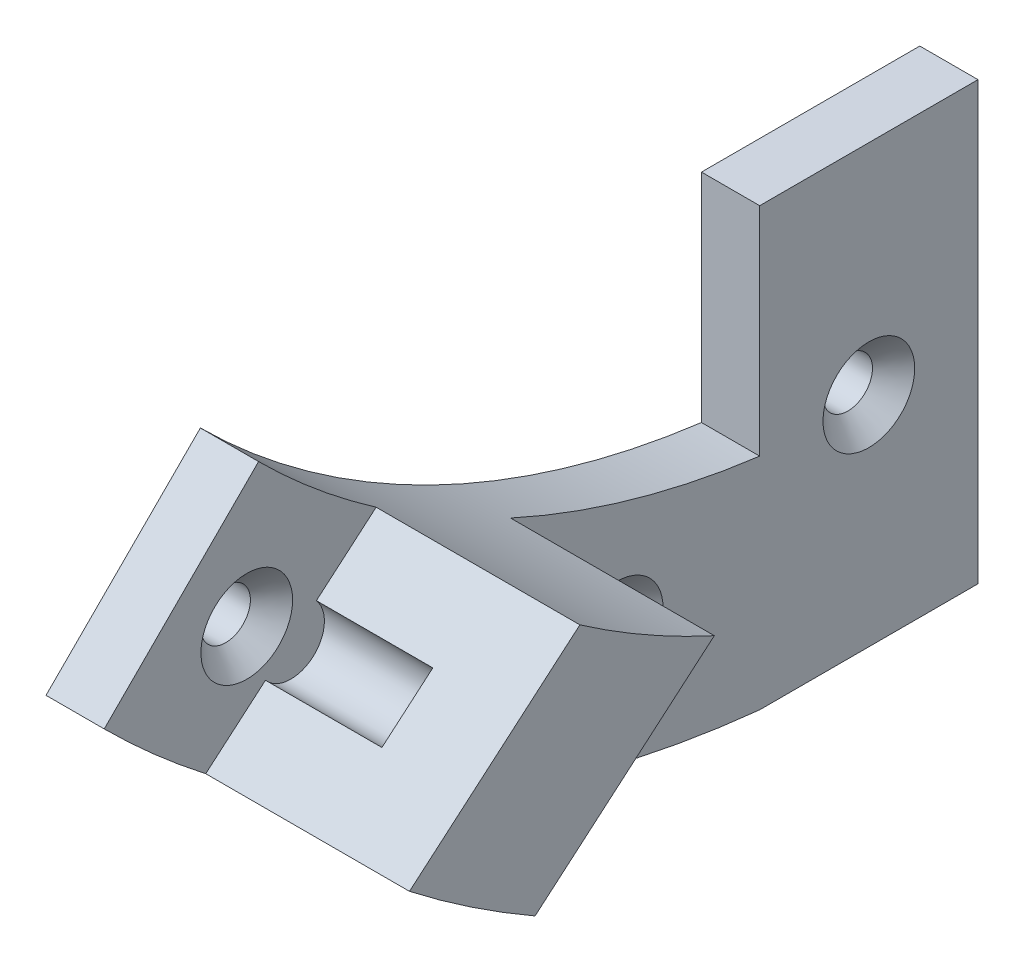
SolidWorks part; units mm, degrees
material "ABS"
ref_plane "Front Plane" through (0, 0, 0) normal (0, 0, 1) x (1, 0, 0)
ref_plane "Top Plane" through (0, 0, 0) normal (0, 1, 0) x (1, 0, 0)
ref_plane "Right Plane" through (0, 0, 0) normal (1, 0, 0) x (0, 0, -1)
sketch "Sketch1" plane through (0, 0, 0) normal (1, 0, 0) x (0, 0, -1)
  line L0 (-52.538, 6.3825) -> (-41.9314, 16.9891)
  line L1 (-7.5, 15) -> (7.5, 15)
  line L2 (-7.5, 15) -> (-7.5, -15)
  line L3 (-7.5, -15) -> (7.5, -15)
  line L4 (7.5, 15) -> (7.5, -15)
  line L5 (-7.5, 15) -> (7.5, -15) construction
  line L6 (-7.5, -15) -> (7.5, 15) construction
  line L7 (-45.5654, 0.2324) -> (-33.857, 10.2359)
  arc A2 (-7.5, -15) -> (-45.5654, 0.2324) centre (0, 58.9205) cw
  arc A3 (-7.5, 0.0967) -> (-41.9314, 16.9891) centre (0, 58.9205) cw
  arc A4 (-45.5654, 0.2324) -> (-52.538, 6.3825) centre (0, 58.9205) cw
  point P0 (0, 0)
  dimension "D3" = 74.3
  dimension "D4" = 45
  dimension "D7" = 15
  dimension "D1" = 15
  dimension "D2" = 30
  dimension "D5" = 41
  dimension "D6" = 49.49
extrude "Boss-Extrude1" add sketch "Sketch1" along normal blind 4
sketch "Sketch2" plane through (4, 0, 0) normal (1, 0, 0) x (0, 0, -1)
  line L0 (-45.5632, 0.2308) -> (-33.8547, 10.2343)
  line L1 (-36.934, -5.5494) -> (-24.6189, 4.9724)
  line L7 (-45.5654, 0.2324) -> (-33.857, 10.2359) construction
  arc A0 (-33.8547, 10.2343) -> (-24.6189, 4.9724) centre (0, 58.9205) ccw
  arc A1 (-45.5632, 0.2308) -> (-36.934, -5.5494) centre (0, 58.9205) ccw
  arc A2 (-41.9314, 16.9891) -> (-7.5, 0.0967) centre (0, 58.9205) ccw construction
  arc A3 (-52.538, 6.3825) -> (-7.5, -15) centre (0, 58.9205) ccw construction
  arc M5 (-52.538, 6.3825) -> (-7.5, -15) centre (0, 58.9205) ccw
  arc M10 (-7.5, 0.0967) -> (-41.9314, 16.9891) centre (0, 58.9205) cw
  dimension "D1" = 10
  dimension "D2" = 33.8547
extrude "Boss-Extrude2" add sketch "Sketch2" along normal blind 14 contours L1 L0 M5 M10
sketch "Sketch3" plane through (4, 0, 0) normal (1, 0, 0) x (0, 0, -1)
  line L1 (-45.5632, 0.2308) -> (-33.8547, 10.2343) construction
  circle A0 centre (-39.709, 5.2325) radius 2.3
  point P4 (0, 0)
  dimension "D1" = 4.6
extrude "Cut-Extrude1" cut sketch "Sketch3" along normal blind 8
hole_wizard "CSK for M3 Flat Head Machine Screw1" positions "Sketch6" profile "Sketch7" countersink size "M3" standard "ANSI Metric"
sketch "Sketch6" plane through (4, 0, 0) normal (1, 0, 0) x (0, 0, -1)
  line L3 (-19.2303, -12.8478) -> (-15.348, 1.6411) construction
  line L4 (-7.5, 15) -> (-7.5, 0.0967) construction
  line L7 (-7.5, 15) -> (7.5, 15) construction
  arc A0 (-24.6189, 4.9724) -> (-7.5, 0.0967) centre (0, 58.9205) ccw construction
  arc A1 (-36.934, -5.5494) -> (-7.5, -15) centre (0, 58.9205) ccw construction
  circle A2 centre (0, 58.9205) radius 59.3
  point P0 (-42.7434, 7.59)
  point P2 (-17.2891, -5.6033)
  point P4 (0, 0)
  point P42 (-17.2891, -5.6033)
  point P76 (0, 0)
  point P79 (-5.4827, 15)
  dimension "D2" = 15
  dimension "D4" = 35.2434
  dimension "D5" = 7.41
sketch "Sketch7" plane through (4, 7.59, 42.7434) normal (0, 1, 0) x (0, 0, -1)
  line L0 (0, 0) -> (0, 7.3715)
  line L1 (0, 7.3715) -> (1.7, 6.35)
  line L2 (1.7, 6.35) -> (1.7, 1.45)
  line L3 (1.7, 1.45) -> (3.15, 0)
  line L5 (3.15, 0) -> (0, 0)
  line L6 (-1.7, 1.45) -> (-3.15, 0) construction
  line L10 (0, 7.3715) -> (-1.7, 6.35) construction
  line L11 (0, -6.35) -> (0, 107.95) construction
  dimension "Hole Dia." = 3.4
  dimension "Hole Depth" = 6.35
  dimension "Near C'Sink Dia." = 6.3
  dimension "Near C'Sink Angle" = 90
  dimension "Drill Angle" = 118
